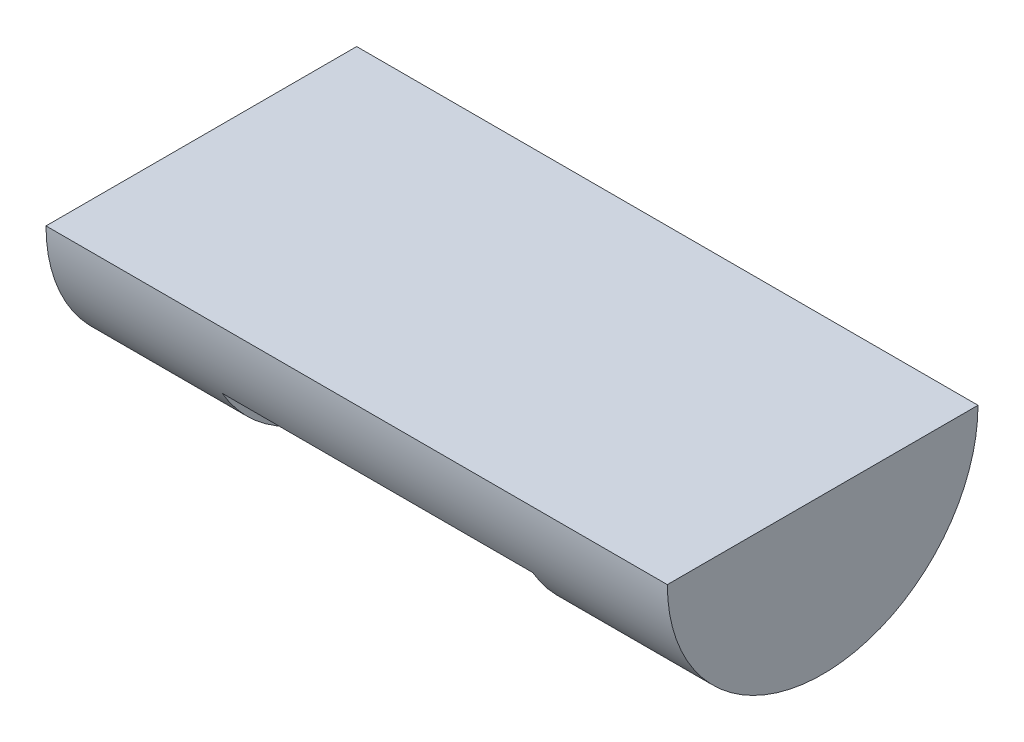
SolidWorks part; units mm, degrees
ref_plane "Front Plane" through (0, 0, 0) normal (0, 0, 1) x (1, 0, 0)
ref_plane "Top Plane" through (0, 0, 0) normal (0, 1, 0) x (1, 0, 0)
ref_plane "Right Plane" through (0, 0, 0) normal (1, 0, 0) x (0, 0, -1)
sketch "Sketch1" plane through (0, 0, 0) normal (1, 0, 0) x (0, 0, -1)
  line L0 (152.4, 0) -> (-152.4, 0)
  arc A0 (-152.4, 0) -> (152.4, 0) centre (0, 0) ccw
  point P4 (0, 0)
  dimension "D1" = 304.8
extrude "Base" add sketch "Sketch1" along normal blind 914.4
sketch "Sketch2" plane through (0, 0, 0) normal (0, 0, 1) x (1, 0, 0)
  line L0 (304.8, -152.4) -> (304.8, -76.2)
  line L1 (0, -152.4) -> (914.4, -152.4) construction
  line L2 (304.8, -76.2) -> (609.6, -76.2)
  line L3 (609.6, -76.2) -> (609.6, -152.4)
  line L4 (609.6, -152.4) -> (304.8, -152.4)
  line L6 (914.4, -152.4) -> (914.4, 0) construction
  dimension "D1" = 76.2
  dimension "D2" = 304.8
  dimension "D3" = 304.8
extrude "Slot" cut sketch "Sketch2" against normal through all both and the other way through all
sketch "Sketch3" plane through (0, 0, 0) normal (-1, 0, 0) x (0, 0, 1)
  line L1 (152.4, 0) -> (-152.4, 0)
  line L2 (152.4, 0) -> (-152.4, 0)
  arc A1 (-152.4, 0) -> (152.4, 0) centre (0, 0) ccw
  arc A2 (-152.4, 0) -> (152.4, 0) centre (0, 0) ccw
  dimension "D1" = 0
extrude "Left Cut" cut sketch "Sketch3" against normal blind 152.4
ref_plane "Midplane" through (457.2, 0, 0) normal (1, 0, 0) x (0, 0, -1)
mirror "Right Cut" about plane through (457.2, 0, 0) normal (1, 0, 0) of "Left Cut"
